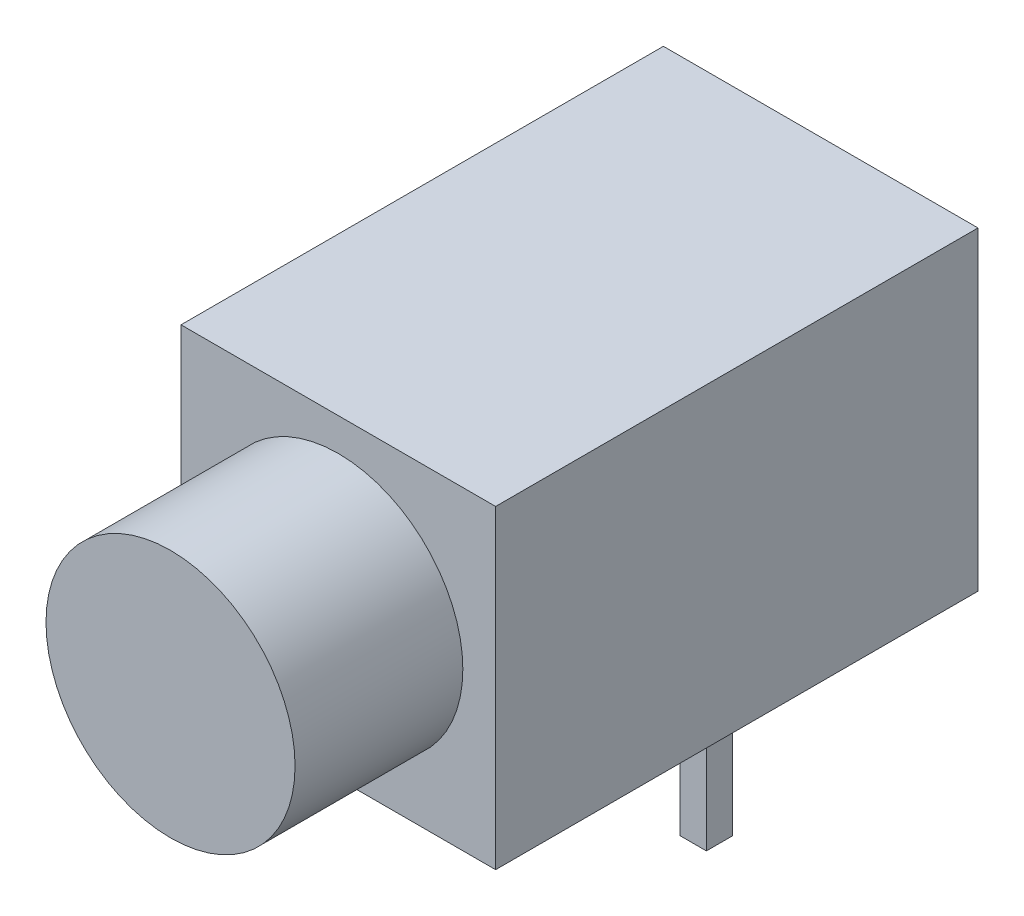
SolidWorks part; units mm, degrees
ref_plane "Front Plane" through (0, 0, 0) normal (0, 0, 1) x (1, 0, 0)
ref_plane "Top Plane" through (0, 0, 0) normal (0, 1, 0) x (1, 0, 0)
ref_plane "Right Plane" through (0, 0, 0) normal (1, 0, 0) x (0, 0, -1)
sketch "Sketch2" plane through (0, 0, 0) normal (0, 1, 0) x (1, 0, 0)
  line L1 (0, 0) -> (6, 0)
  line L2 (0, 0) -> (0, 9.2)
  line L3 (0, 9.2) -> (6, 9.2)
  line L4 (6, 0) -> (6, 9.2)
  dimension "D1" = 6
  dimension "D2" = 9.2
extrude "Boss-Extrude1" add sketch "Sketch2" along normal blind 6 contours L2 L1 L4 L3
sketch "Sketch3" plane through (0, 0, 0) normal (0, 0, 1) x (1, 0, 0)
  line L0 (0, 6) -> (6, 6) construction
  circle A0 centre (3, 3) radius 2.375
  point P2 (3.0378, 3.146)
  point P5 (3, 6)
  point P6 (0, 0)
  dimension "D1" = 4.75
  dimension "D2" = 3
extrude "Boss-Extrude2" add sketch "Sketch3" along normal blind 3.2
sketch "Sketch4" plane through (0, 0, 0) normal (0, -1, 0) x (1, 0, 0)
  line L0 (0, 0) -> (6, 0) construction
  line L1 (1.48, -6) -> (1.98, -6)
  line L2 (1.48, -6) -> (1.48, -5.5)
  line L3 (1.48, -5.5) -> (1.98, -5.5)
  line L4 (1.98, -6) -> (1.98, -5.5)
  line L5 (4.02, -6) -> (4.52, -6)
  line L6 (4.02, -6) -> (4.02, -5.5)
  line L7 (4.02, -5.5) -> (4.52, -5.5)
  line L8 (4.52, -6) -> (4.52, -5.5)
  line L9 (0, 0) -> (0, -9.2) construction
  line L10 (6, 0) -> (6, -9.2) construction
  point P10 (1.73, -6)
  point P11 (4.27, -6)
  dimension "D1" = 5.5
  dimension "D2" = 5.5
  dimension "D3" = 0.5
  dimension "D4" = 0.5
  dimension "D5" = 0.5
  dimension "D6" = 0.5
  dimension "D7" = 2.54
  dimension "D8" = 1.48
  dimension "D9" = 1.48
extrude "Boss-Extrude3" add sketch "Sketch4" along normal blind 3.18
